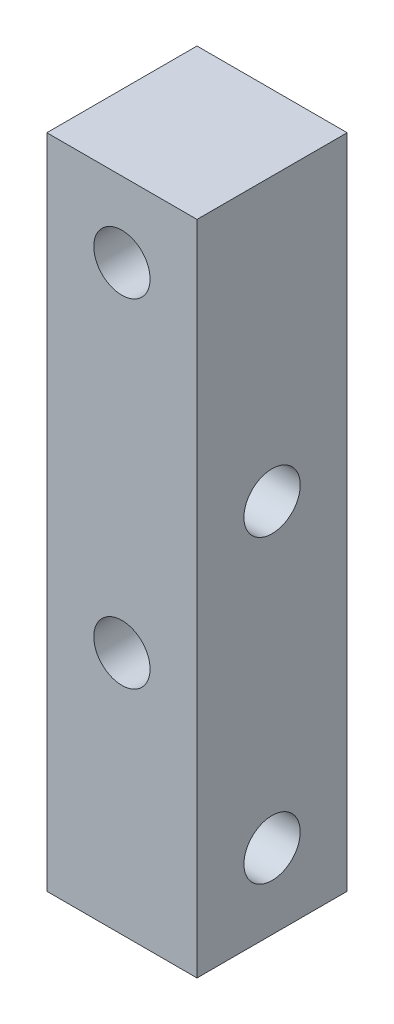
SolidWorks part; units mm, degrees
material "ABS PC"
ref_plane "Front Plane" through (0, 0, 0) normal (0, 0, 1) x (1, 0, 0)
ref_plane "Top Plane" through (0, 0, 0) normal (0, 1, 0) x (1, 0, 0)
ref_plane "Right Plane" through (0, 0, 0) normal (1, 0, 0) x (0, 0, -1)
sketch "Sketch1" plane through (0, 0, 0) normal (0, 1, 0) x (1, 0, 0)
  line L1 (-4, 4) -> (4, 4)
  line L2 (-4, 4) -> (-4, -4)
  line L3 (-4, -4) -> (4, -4)
  line L4 (4, 4) -> (4, -4)
  line L5 (-4, 4) -> (4, -4) construction
  line L6 (-4, -4) -> (4, 4) construction
  point P0 (0, 0)
  dimension "D1" = 8
  dimension "D2" = 8
extrude "Boss-Extrude1" add sketch "Sketch1" along normal blind 35
sketch "Sketch2" plane through (0, 0, -4) normal (0, 0, -1) x (-1, 0, 0)
  line L0 (-4, 35) -> (4, 35) construction
  circle A0 centre (0, 31) radius 1.5
  circle A1 centre (0, 13) radius 1.5
  dimension "D1" = 3
  dimension "D2" = 4
  dimension "D3" = 18
extrude "Cut-Extrude1" cut sketch "Sketch2" against normal through all
sketch "Sketch3" plane through (4, 0, 0) normal (1, 0, 0) x (0, 0, -1)
  line L0 (-4, 0) -> (4, 0) construction
  circle A0 centre (0, 20) radius 1.5
  circle A1 centre (0, 4) radius 1.5
  point P7 (0, 0)
  dimension "D1" = 3
  dimension "D2" = 16
  dimension "D3" = 4
extrude "Cut-Extrude2" cut sketch "Sketch3" against normal through all
